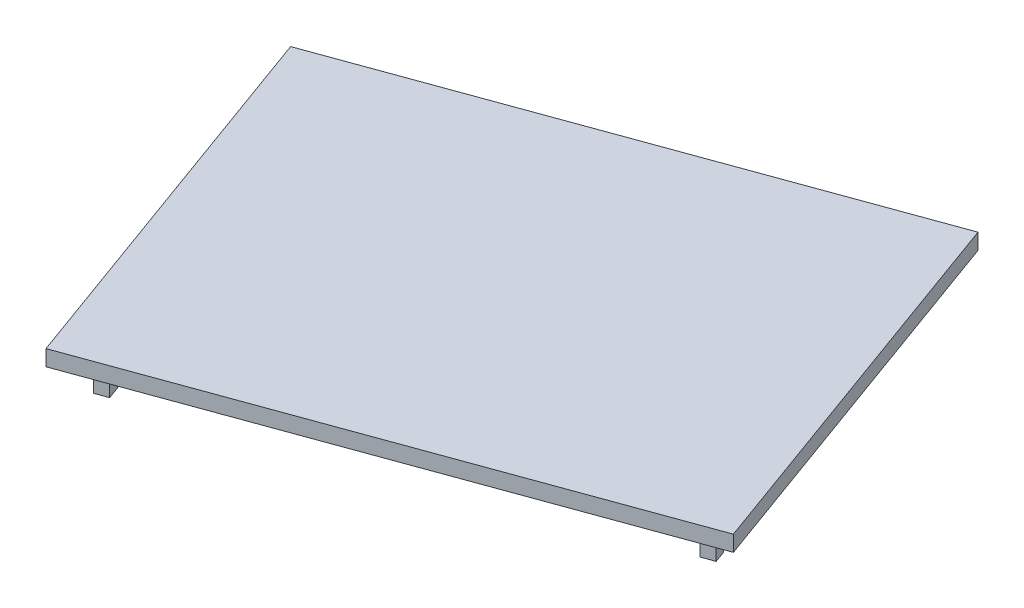
SolidWorks part; units mm, degrees
ref_plane "前视基准面" through (0, 0, 0) normal (0, 0, 1) x (1, 0, 0)
ref_plane "上视基准面" through (0, 0, 0) normal (0, 1, 0) x (1, 0, 0)
ref_plane "右视基准面" through (0, 0, 0) normal (1, 0, 0) x (0, 0, -1)
sketch "草图1" plane through (0, 0, 0) normal (0, 1, 0) x (1, 0, 0)
  line L0 (-86.5893, 24.6335) -> (-90.3495, 23.2695)
  line L1 (-57.8495, -89.7905) -> (101.9619, -31.8224)
  line L2 (101.9619, -31.8224) -> (57.8495, 89.7905)
  line L3 (57.8495, 89.7905) -> (-101.9619, 31.8224)
  line L4 (-101.9619, 31.8224) -> (-57.8495, -89.7905)
  line L5 (-86.5893, 24.6335) -> (-87.9528, 28.3926)
  line L6 (86.156, -32.2369) -> (-45.4534, -79.9754)
  line L7 (-45.4534, -79.9754) -> (-48.8633, -70.5747)
  line L8 (-48.8633, -70.5747) -> (-58.264, -73.9846)
  line L9 (-58.264, -73.9846) -> (-92.1468, 19.4264)
  line L10 (-92.1468, 19.4264) -> (-82.7461, 22.8363)
  line L11 (-82.7461, 22.8363) -> (-86.156, 32.2369)
  line L12 (-86.156, 32.2369) -> (45.4534, 79.9754)
  line L13 (45.4534, 79.9754) -> (48.8633, 70.5747)
  line L14 (48.8633, 70.5747) -> (58.264, 73.9846)
  line L15 (58.264, 73.9846) -> (92.1468, -19.4264)
  line L16 (82.7461, -22.8363) -> (86.156, -32.2369)
  line L17 (-90.3495, 23.2695) -> (-91.7131, 27.0287)
  line L18 (-87.9528, 28.3926) -> (-91.7131, 27.0287)
  line L19 (-49.2966, -78.1781) -> (-53.0568, -79.5421)
  line L20 (-49.2966, -78.1781) -> (-50.6674, -74.3989)
  line L21 (-53.0568, -79.5421) -> (-54.4277, -75.7629)
  line L22 (-50.6674, -74.3989) -> (-54.4277, -75.7629)
  line L23 (91.7135, -27.0298) -> (87.9532, -28.3938)
  line L24 (91.7135, -27.0298) -> (90.3573, -23.291)
  line L25 (87.9532, -28.3938) -> (86.5971, -24.6549)
  line L26 (90.3573, -23.291) -> (86.5971, -24.6549)
  line L27 (54.4208, 75.7818) -> (50.6606, 74.4179)
  line L28 (54.4208, 75.7818) -> (53.0284, 79.6207)
  line L29 (50.6606, 74.4179) -> (49.2681, 78.2567)
  line L30 (53.0284, 79.6207) -> (49.2681, 78.2567)
  point P32 (0, 0)
sketch "草图2" plane through (0, 0, 0) normal (0, 1, 0) x (1, 0, 0)
  line L0 (-101.9619, 31.8224) -> (57.8495, 89.7905)
  line L1 (57.8495, 89.7905) -> (101.9619, -31.8224)
  line L2 (101.9619, -31.8224) -> (-57.8495, -89.7905)
  line L3 (-57.8495, -89.7905) -> (-101.9619, 31.8224)
extrude "凸台-拉伸1" add sketch "草图2" along normal blind 5
sketch "草图3" plane through (0, 0, 0) normal (0, 1, 0) x (1, 0, 0)
  line L0 (-53.0568, -79.5421) -> (-49.2966, -78.1781)
  line L1 (-53.0568, -79.5421) -> (-54.5213, -75.5049)
  line L2 (-49.2966, -78.1781) -> (-50.761, -74.1409)
  line L3 (-54.5213, -75.5049) -> (-50.761, -74.1409)
  line L4 (87.9532, -28.3938) -> (91.7135, -27.0298)
  line L5 (87.9532, -28.3938) -> (86.6045, -24.6755)
  line L6 (91.7135, -27.0298) -> (90.3648, -23.3116)
  line L7 (86.6045, -24.6755) -> (90.3648, -23.3116)
  line L8 (50.6606, 74.4179) -> (54.4208, 75.7818)
  line L9 (50.6606, 74.4179) -> (49.2978, 78.1749)
  line L10 (54.4208, 75.7818) -> (53.0581, 79.5388)
  line L11 (49.2978, 78.1749) -> (53.0581, 79.5388)
  line L12 (-90.3495, 23.2695) -> (-86.5893, 24.6335)
  line L13 (-90.3495, 23.2695) -> (-91.7296, 27.0743)
  line L14 (-86.5893, 24.6335) -> (-87.9694, 28.4383)
  line L15 (-91.7296, 27.0743) -> (-87.9694, 28.4383)
extrude "凸台-拉伸2" add sketch "草图3" against normal blind 10
